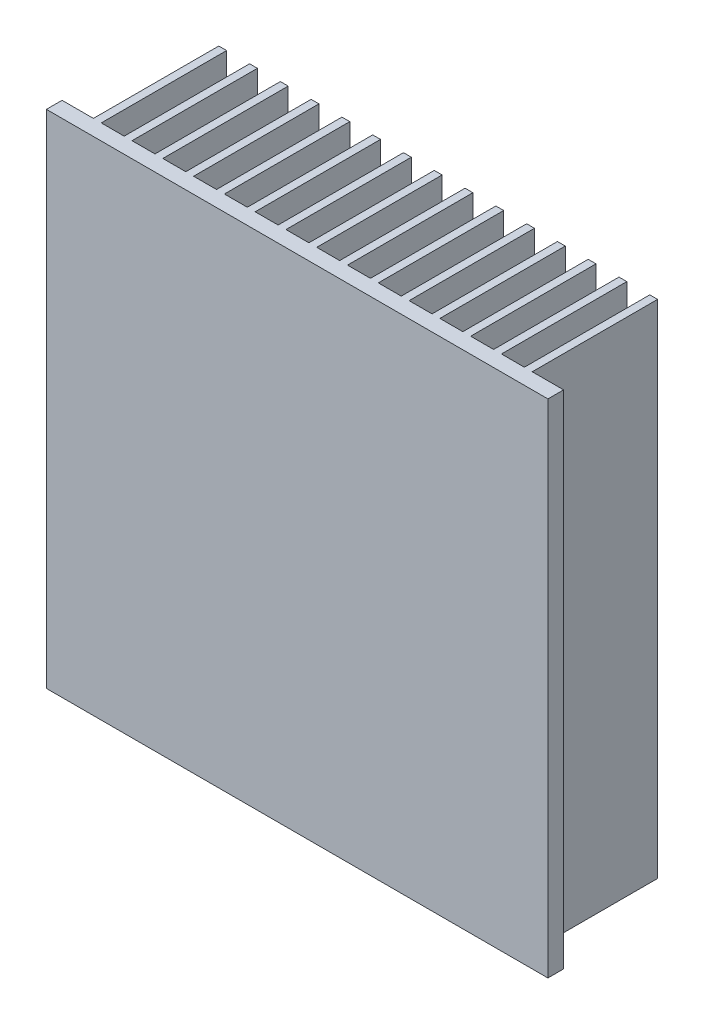
SolidWorks part; units mm, degrees
material "3003 Alloy"
ref_plane "Front Plane" through (0, 0, 0) normal (0, 0, 1) x (1, 0, 0)
ref_plane "Top Plane" through (0, 0, 0) normal (0, 1, 0) x (1, 0, 0)
ref_plane "Right Plane" through (0, 0, 0) normal (1, 0, 0) x (0, 0, -1)
sketch "Sketch1" plane through (0, 0, 0) normal (0, 1, 0) x (1, 0, 0)
  line L0 (-38.2134, 3.175) -> (-38.2134, 28.575)
  line L1 (-50.8, 0) -> (50.8, 0)
  line L2 (-50.8, 0) -> (-50.8, 3.175)
  line L3 (-50.8, 3.175) -> (-44.45, 3.175)
  line L4 (50.8, 0) -> (50.8, 3.175)
  line L6 (-44.45, 3.175) -> (-44.45, 28.575)
  line L7 (-44.45, 28.575) -> (-42.8625, 28.575)
  line L8 (-42.8625, 3.175) -> (-42.8625, 28.575)
  line L9 (-36.6259, 3.175) -> (-36.6259, 28.575)
  line L10 (-38.2134, 28.575) -> (-36.6259, 28.575)
  line L11 (-31.9768, 3.175) -> (-31.9768, 28.575)
  line L12 (-30.3893, 3.175) -> (-30.3893, 28.575)
  line L13 (-31.9768, 28.575) -> (-30.3893, 28.575)
  line L14 (-25.7402, 3.175) -> (-25.7402, 28.575)
  line L15 (-24.1527, 3.175) -> (-24.1527, 28.575)
  line L16 (-25.7402, 28.575) -> (-24.1527, 28.575)
  line L17 (-19.5036, 3.175) -> (-19.5036, 28.575)
  line L18 (-17.9161, 3.175) -> (-17.9161, 28.575)
  line L19 (-19.5036, 28.575) -> (-17.9161, 28.575)
  line L20 (-13.267, 3.175) -> (-13.267, 28.575)
  line L21 (-11.6795, 3.175) -> (-11.6795, 28.575)
  line L22 (-13.267, 28.575) -> (-11.6795, 28.575)
  line L23 (-7.0304, 3.175) -> (-7.0304, 28.575)
  line L24 (-5.4429, 3.175) -> (-5.4429, 28.575)
  line L25 (-7.0304, 28.575) -> (-5.4429, 28.575)
  line L26 (-0.7938, 3.175) -> (-0.7938, 28.575)
  line L27 (0.7937, 3.175) -> (0.7937, 28.575)
  line L28 (-0.7938, 28.575) -> (0.7937, 28.575)
  line L29 (5.4429, 3.175) -> (5.4429, 28.575)
  line L30 (7.0304, 3.175) -> (7.0304, 28.575)
  line L31 (5.4429, 28.575) -> (7.0304, 28.575)
  line L32 (11.6795, 3.175) -> (11.6795, 28.575)
  line L33 (13.267, 3.175) -> (13.267, 28.575)
  line L34 (11.6795, 28.575) -> (13.267, 28.575)
  line L35 (17.9161, 3.175) -> (17.9161, 28.575)
  line L36 (19.5036, 3.175) -> (19.5036, 28.575)
  line L37 (17.9161, 28.575) -> (19.5036, 28.575)
  line L38 (24.1527, 3.175) -> (24.1527, 28.575)
  line L39 (25.7402, 3.175) -> (25.7402, 28.575)
  line L40 (24.1527, 28.575) -> (25.7402, 28.575)
  line L41 (30.3893, 3.175) -> (30.3893, 28.575)
  line L42 (31.9768, 3.175) -> (31.9768, 28.575)
  line L43 (30.3893, 28.575) -> (31.9768, 28.575)
  line L44 (36.6259, 3.175) -> (36.6259, 28.575)
  line L45 (38.2134, 3.175) -> (38.2134, 28.575)
  line L46 (36.6259, 28.575) -> (38.2134, 28.575)
  line L47 (42.8625, 3.175) -> (42.8625, 28.575)
  line L48 (44.45, 3.175) -> (44.45, 28.575)
  line L49 (42.8625, 28.575) -> (44.45, 28.575)
  line L50 (44.45, 3.175) -> (50.8, 3.175)
  line L51 (38.2134, 3.175) -> (42.8625, 3.175)
  line L52 (31.9768, 3.175) -> (36.6259, 3.175)
  line L53 (25.7402, 3.175) -> (30.3893, 3.175)
  line L54 (19.5036, 3.175) -> (24.1527, 3.175)
  line L55 (13.267, 3.175) -> (17.9161, 3.175)
  line L56 (7.0304, 3.175) -> (11.6795, 3.175)
  line L57 (0.7937, 3.175) -> (5.4429, 3.175)
  line L58 (-5.4429, 3.175) -> (-0.7938, 3.175)
  line L59 (-11.6795, 3.175) -> (-7.0304, 3.175)
  line L60 (-17.9161, 3.175) -> (-13.267, 3.175)
  line L61 (-24.1527, 3.175) -> (-19.5036, 3.175)
  line L62 (-30.3893, 3.175) -> (-25.7402, 3.175)
  line L63 (-36.6259, 3.175) -> (-31.9768, 3.175)
  line L64 (-42.8625, 3.175) -> (-38.2134, 3.175)
  dimension "D1" = 3.175
  dimension "D2" = 6.35
  dimension "D3" = 1.5875
  dimension "D4" = 25.4
  dimension "D5" = 6.35
  dimension "D6" = 15
extrude "Boss-Extrude1" add sketch "Sketch1" along normal blind 101.6
